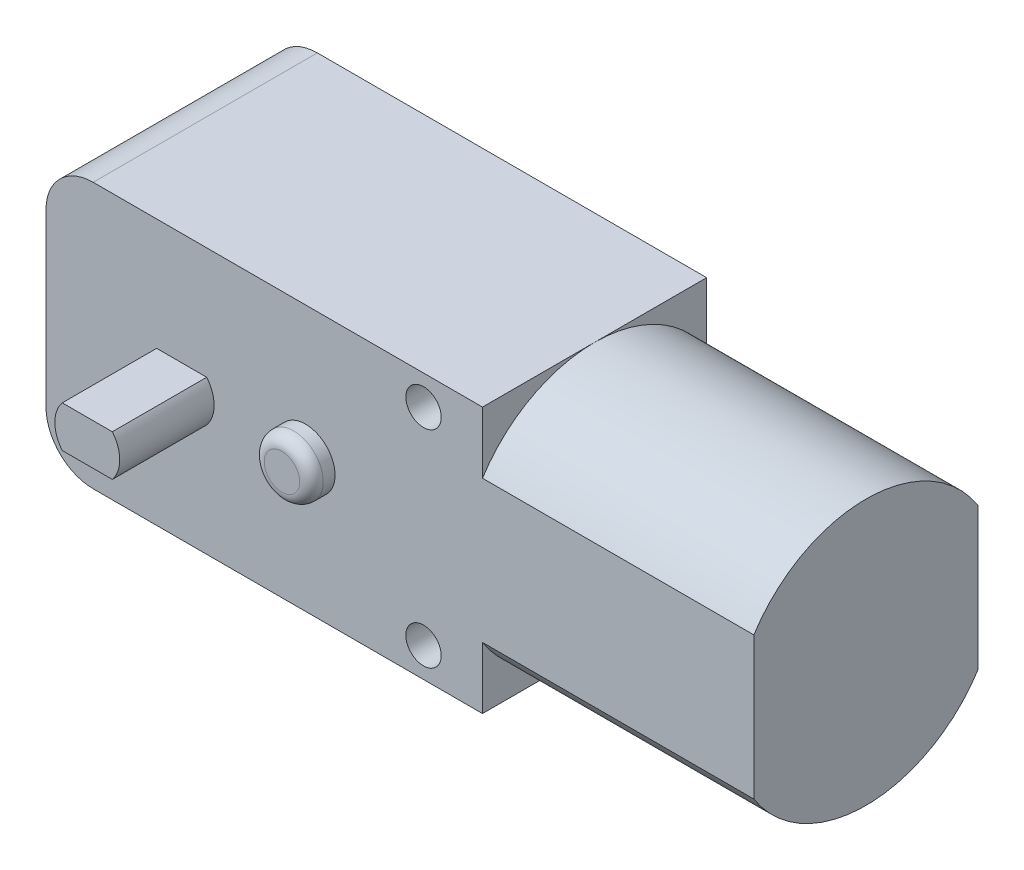
SolidWorks part; units mm, degrees
ref_plane "Front Plane" through (0, 0, 0) normal (0, 0, 1) x (1, 0, 0)
ref_plane "Top Plane" through (0, 0, 0) normal (0, 1, 0) x (1, 0, 0)
ref_plane "Right Plane" through (0, 0, 0) normal (1, 0, 0) x (0, 0, -1)
sketch "Sketch1" plane through (0, 0, 0) normal (0, 0, 1) x (1, 0, 0)
  line L1 (-14.5, 11.25) -> (18.5, 11.25)
  line L2 (-18.5, 7.25) -> (-18.5, -7.25)
  line L3 (-14.5, -11.25) -> (18.5, -11.25)
  line L4 (18.5, 11.25) -> (18.5, -11.25)
  line L5 (-18.5, 11.25) -> (18.5, -11.25) construction
  line L6 (-18.5, -11.25) -> (18.5, 11.25) construction
  arc A0 (-18.5, -7.25) -> (-14.5, -11.25) centre (-14.5, -7.25) ccw
  arc A1 (-14.5, 11.25) -> (-18.5, 7.25) centre (-14.5, 7.25) ccw
  point P0 (0, 0)
  dimension "D3" = 4
  dimension "D1" = 22.5
  dimension "D2" = 37
extrude "Boss-Extrude1" add sketch "Sketch1" along normal blind 19
sketch "Sketch2" plane through (18.5, 0, 0) normal (1, 0, 0) x (0, 0, -1)
  line L0 (0, 0) -> (-19, 0) construction
  line L1 (-19, -11.25) -> (-19, 11.25) construction
  line L2 (-19, 6.026) -> (-19, -6.026)
  line L3 (0, -6.026) -> (0, 6.026)
  line L4 (0, -11.25) -> (0, 11.25) construction
  arc A0 (-19, -6.026) -> (0, -6.026) centre (-9.5, 0) ccw
  arc A1 (0, 6.026) -> (-19, 6.026) centre (-9.5, 0) ccw
extrude "Boss-Extrude2" add sketch "Sketch2" along normal blind 23
sketch "Sketch3" plane through (0, 0, 19) normal (0, 0, 1) x (1, 0, 0)
  line L0 (-18.5, 0) -> (-7, 0) construction
  line L1 (-18.5, 7.25) -> (-18.5, -7.25) construction
  line L3 (-9.1213, 1.75) -> (-4.8787, 1.75)
  line L5 (-9.1213, -1.75) -> (-4.8787, -1.75)
  line L7 (-9.1213, 1.75) -> (-4.8787, -1.75) construction
  line L8 (-9.1213, -1.75) -> (-4.8787, 1.75) construction
  arc A0 (-9.1213, 1.75) -> (-9.1213, -1.75) centre (-7, 0) ccw
  arc A1 (-4.8787, -1.75) -> (-4.8787, 1.75) centre (-7, 0) ccw
  dimension "D1" = 11.5
  dimension "D2" = 5.5
  dimension "D3" = 3.5
extrude "Boss-Extrude3" add sketch "Sketch3" along normal blind 8
sketch "Sketch4" plane through (0, 0, 19) normal (0, 0, 1) x (1, 0, 0)
  line L0 (-7, 0) -> (3.5, 0) construction
  circle A0 centre (3.5, 0) radius 2.5
  dimension "D2" = 5
  dimension "D1" = 10.5
extrude "Boss-Extrude4" add sketch "Sketch4" along normal blind 2
fillet "Fillet1" radius 1 1 edges at (6, 0, 21)
sketch "Sketch5" plane through (0, 0, 19) normal (0, 0, 1) x (1, 0, 0)
  line L0 (13.5, 8.75) -> (13.5, -8.75) construction
  line L1 (13.5, 0) -> (3.5, 0) construction
  line L2 (18.5, 6.026) -> (18.5, 11.25) construction
  line L3 (18.5, 11.25) -> (-14.5, 11.25) construction
  circle A0 centre (13.5, 8.75) radius 1.5
  circle A1 centre (13.5, -8.75) radius 1.5
  dimension "D3" = 3
  dimension "D1" = 5
  dimension "D2" = 2.5
extrude "Cut-Extrude1" cut sketch "Sketch5" against normal through all
